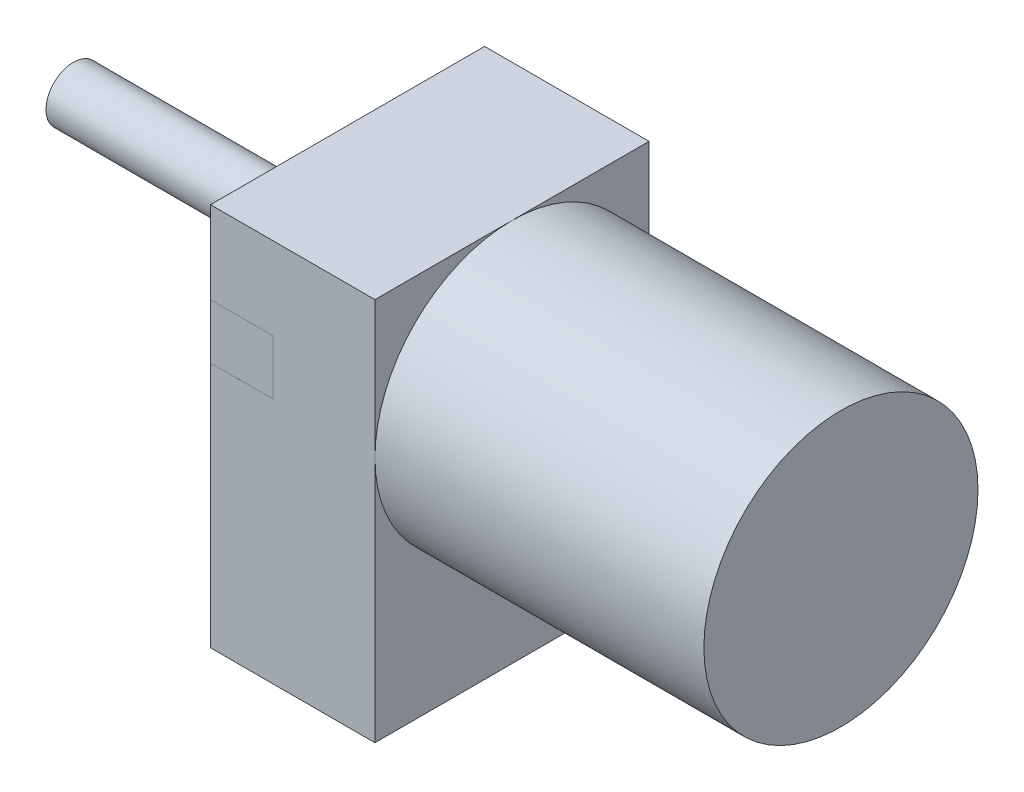
SolidWorks part; units mm, degrees
ref_plane "Plan de face" through (0, 0, 0) normal (0, 0, 1) x (1, 0, 0)
ref_plane "Plan de dessus" through (0, 0, 0) normal (0, 1, 0) x (1, 0, 0)
ref_plane "Plan de droite" through (0, 0, 0) normal (1, 0, 0) x (0, 0, -1)
sketch "Esquisse1" plane through (0, 0, 0) normal (0, 0, 1) x (1, 0, 0)
  line L1 (0, 0) -> (-15, 0)
  line L2 (0, 0) -> (0, 35)
  line L3 (0, 35) -> (-15, 35)
  line L4 (-15, 0) -> (-15, 35)
  dimension "D1" = 15
  dimension "D2" = 35
extrude "Extrusion1" add sketch "Esquisse1" along normal blind 25
sketch "Esquisse2" plane through (0, 0, 0) normal (1, 0, 0) x (0, 0, -1)
  line L0 (-12.5, 22.5) -> (-12.5, 35) construction
  line L1 (-25, 35) -> (0, 35) construction
  circle A0 centre (-12.5, 22.5) radius 12.5
  dimension "D2" = 25
  dimension "D1" = 12.5
extrude "Extrusion2" add sketch "Esquisse2" along normal blind 30
sketch "Esquisse3" plane through (-15, 0, 0) normal (-1, 0, 0) x (0, 0, 1)
  line L0 (25, 35) -> (0, 35) construction
  line L1 (25, 35) -> (25, 0) construction
  circle A0 centre (12.5, 25) radius 2.5
  dimension "D3" = 5
  dimension "D1" = 10
  dimension "D2" = 12.5
extrude "Extrusion4" add sketch "Esquisse3" along normal blind 25
sketch "Esquisse4" plane through (0, 0, 25) normal (0, 0, 1) x (1, 0, 0)
  line L0 (-40, 25) -> (-3.5226, 25) construction
  line L1 (-40, 27.5) -> (-40, 22.5) construction
  line L2 (-15, 27.5) -> (-15, 22.5) construction
  line L3 (-15, 27.5) -> (-9.2958, 27.5)
  line L4 (-15, 27.5) -> (-15, 22.5)
  line L5 (-15, 22.5) -> (-9.2958, 22.5)
  line L6 (-9.2958, 27.5) -> (-9.2958, 22.5)
  dimension "D1" = 2.5
  dimension "D2" = 5
extrude "Enlèv. mat.-Extru.1" cut sketch "Esquisse4" against normal blind 0.0001
sketch "Esquisse5" plane through (0, 0, 0) normal (0, 0, -1) x (-1, 0, 0)
  line L0 (-13.9938, 24.9487) -> (22.4836, 24.9487) construction
  line L1 (9.2776, 27.4487) -> (14.9818, 27.4487)
  line L2 (9.2776, 27.4487) -> (9.2776, 22.4487)
  line L3 (9.2776, 22.4487) -> (14.9818, 22.4487)
  line L4 (14.9818, 27.4487) -> (14.9818, 22.4487)
  dimension "D1" = 2.5
  dimension "D2" = 5
extrude "Enlèv. mat.-Extru.2" cut sketch "Esquisse5" against normal blind 0.0001
